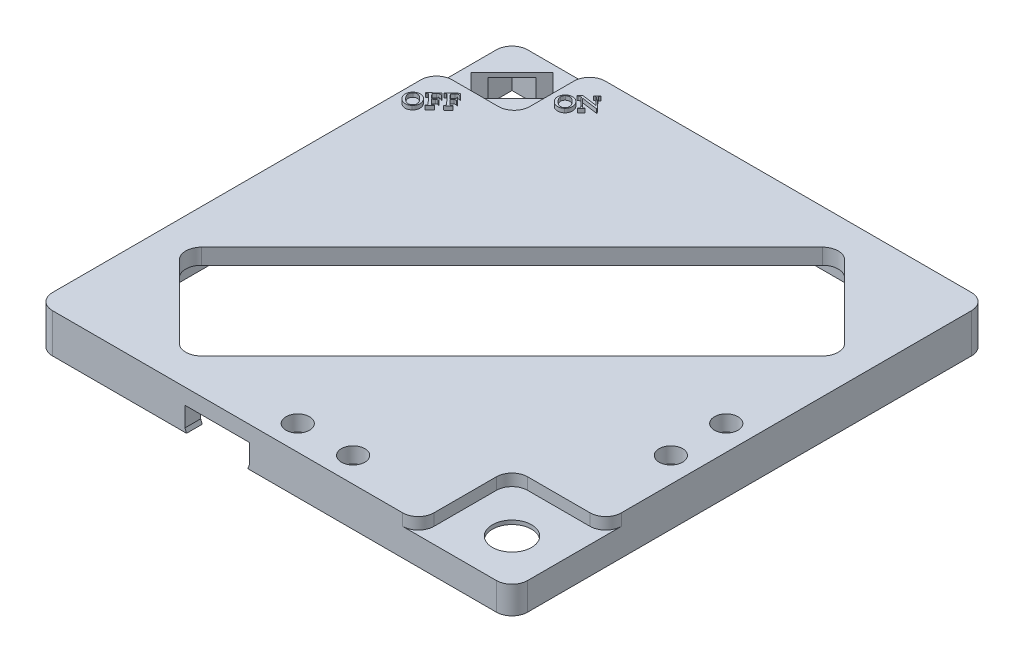
SolidWorks part; units mm, degrees
ref_plane "Front Plane" through (0, 0, 0) normal (0, 0, 1) x (1, 0, 0)
ref_plane "Top Plane" through (0, 0, 0) normal (0, 1, 0) x (1, 0, 0)
ref_plane "Right Plane" through (0, 0, 0) normal (1, 0, 0) x (0, 0, -1)
sketch "Sketch3" plane through (0, 0, 0) normal (0, 1, 0) x (1, 0, 0)
  line L1 (-30.3, -30.3) -> (30.3, -30.3)
  line L2 (-30.3, -30.3) -> (-30.3, 30.3)
  line L3 (-30.3, 30.3) -> (30.3, 30.3)
  line L4 (30.3, -30.3) -> (30.3, 30.3)
  line L5 (-30.3, -30.3) -> (30.3, 30.3) construction
  line L6 (-30.3, 30.3) -> (30.3, -30.3) construction
  point P0 (0, 0)
  dimension "D2" = 60.6
  dimension "D1" = 60.6
extrude "Boss-Extrude1" add sketch "Sketch3" along normal blind 5
sketch "Sketch4" plane through (0, 5, 0) normal (0, 1, 0) x (1, 0, 0)
  line L0 (-15.2028, -27.2236) -> (27.2236, 15.2028)
  line L1 (-15.2028, -27.2236) -> (-27.2236, -15.2028)
  line L2 (27.2236, 15.2028) -> (15.2028, 27.2236)
  line L3 (-27.2236, -15.2028) -> (15.2028, 27.2236)
  line L4 (-15.2028, -27.2236) -> (15.2028, 27.2236) construction
  line L5 (27.2236, 15.2028) -> (-27.2236, -15.2028) construction
  line L6 (30.3, 30.3) -> (-30.3, -30.3) construction
  point P1 (0, 0)
  dimension "D1" = 60
  dimension "D2" = 17
extrude "Cut-Extrude1" cut sketch "Sketch4" against normal through all
sketch "Sketch7" plane through (0, 0, 0) normal (0, -1, 0) x (1, 0, 0)
  line L0 (-30.3, -30.3) -> (-30.3, 30.3) construction
  line L1 (28.3, 28.3) -> (-28.3, 28.3)
  line L2 (28.3, 28.3) -> (28.3, -28.3)
  line L3 (28.3, -28.3) -> (-28.3, -28.3)
  line L4 (-28.3, 28.3) -> (-28.3, -28.3)
  line L5 (28.3, 28.3) -> (-28.3, -28.3) construction
  line L6 (28.3, -28.3) -> (-28.3, 28.3) construction
  line L7 (30.3, -30.3) -> (-30.3, -30.3) construction
  point P0 (0, 0)
  dimension "D1" = 2
  dimension "D2" = 2
extrude "Cut-Extrude11" cut sketch "Sketch7" against normal blind 3
sketch "Sketch9" plane through (0, 3, 0) normal (0, -1, 0) x (1, 0, 0)
  line L0 (30.3, 30.3) -> (-30.3, -30.3) construction
  line L1 (-30.3, 30.3) -> (30.3, 30.3) construction
  line L2 (30.3, 30.3) -> (30.3, -30.3) construction
  line L3 (30.3, 3.33) -> (24.6397, 3.33) construction
  circle A0 centre (27.12, -0.2) radius 1.5
  circle A1 centre (27.12, 6.86) radius 1.5
  circle A2 centre (6.86, 27.12) radius 1.5
  circle A3 centre (-0.2, 27.12) radius 1.5
  dimension "D1" = 3
  dimension "D2" = 30
  dimension "D3" = 3.18
  dimension "D4" = 3.53
extrude "Cut-Extrude12" cut sketch "Sketch9" against normal through all
sketch "Sketch11" plane through (0, 3, 0) normal (0, -1, 0) x (1, 0, 0)
  line L0 (-30.3, -30.3) -> (30.3, 30.3) construction
  line L1 (24.3957, 29.1333) -> (29.1333, 24.3957)
  line L2 (24.3957, 29.1333) -> (19.658, 24.3957)
  line L3 (29.1333, 24.3957) -> (24.3957, 19.658)
  line L4 (19.658, 24.3957) -> (24.3957, 19.658)
  line L5 (24.3957, 29.1333) -> (24.3957, 19.658) construction
  line L6 (29.1333, 24.3957) -> (19.658, 24.3957) construction
  line L7 (-26.5523, -21.3197) -> (-21.3197, -26.5523)
  line L8 (-26.5523, -21.3197) -> (-29.3808, -24.1482)
  line L9 (-21.3197, -26.5523) -> (-24.1482, -29.3808)
  line L10 (-29.3808, -24.1482) -> (-24.1482, -29.3808)
  line L11 (-26.5523, -21.3197) -> (-24.1482, -29.3808) construction
  line L12 (-21.3197, -26.5523) -> (-29.3808, -24.1482) construction
  point P4 (0, 0)
  point P5 (24.3957, 24.3957)
  point P6 (-25.3503, -25.3503)
  dimension "D1" = 6.7
  dimension "D2" = 6.7
  dimension "D3" = 5
  dimension "D4" = 7.4
  dimension "D5" = 4
  dimension "D6" = 5
sketch "Sketch12" plane through (0, 0, 0) normal (0, -1, 0) x (1, 0, 0)
  line L0 (30.3, -30.3) -> (-30.3, -30.3) construction
  line L1 (-30.3, -30.3) -> (-30.3, 30.3) construction
  circle A0 centre (-21.6, -9.72) radius 2.75
  dimension "D1" = 5.5
  dimension "D2" = 20.58
  dimension "D3" = 8.7
extrude "Cut-Extrude14" cut sketch "Sketch12" against normal blind 4.5
sketch "Sketch16" plane through (0, 3, 0) normal (0, -1, 0) x (-1, 0, 0)
  line L0 (-25.7025, 2.9823) -> (-25.7025, 0.2177)
  line L1 (-25.12, -5.46) -> (-25.12, 1.6) construction
  line L2 (-25.12, -1.93) -> (-21.6271, -1.93) construction
  line L3 (-25.7025, -6.8423) -> (-25.7025, -4.0777)
  line L4 (-30.3, -30.3) -> (30.3, 30.3) construction
  line L6 (2.9823, -25.7025) -> (0.2177, -25.7025)
  arc A0 (-25.7025, 0.2177) -> (-25.7025, 2.9823) centre (-25.12, 1.6) ccw
  circle A1 centre (-27.12, 0.2) radius 1.5 construction
  arc A2 (-25.7025, -4.0777) -> (-25.7025, -6.8423) centre (-25.12, -5.46) cw
  arc A4 (0.2177, -25.7025) -> (2.9823, -25.7025) centre (1.6, -25.12) cw
sketch "Sketch17" plane through (0, 3, 0) normal (0, -1, 0) x (1, 0, 0)
  line L0 (18.3515, 18.3515) -> (30.3, 18.3515)
  line L1 (18.3515, 18.3515) -> (18.3515, 30.3)
  line L2 (30.3, 18.3515) -> (30.3, 30.3)
  line L3 (18.3515, 30.3) -> (30.3, 30.3)
  line L4 (18.3515, 18.3515) -> (30.3, 30.3) construction
  line L5 (30.3, 18.3515) -> (18.3515, 30.3) construction
  line L6 (-20.4005, -20.6734) -> (-30.3, -20.6734)
  line L7 (-20.4005, -20.6734) -> (-20.4005, -30.3)
  line L8 (-30.3, -20.6734) -> (-30.3, -30.3)
  line L9 (-20.4005, -30.3) -> (-30.3, -30.3)
  line L10 (-20.4005, -20.6734) -> (-30.3, -30.3) construction
  line L11 (-30.3, -20.6734) -> (-20.4005, -30.3) construction
  line L12 (-30.3, 30.3) -> (30.3, 30.3) construction
  line L13 (30.3, 30.3) -> (30.3, -30.3) construction
  line L14 (30.3, -30.3) -> (-30.3, -30.3) construction
  line L15 (-30.3, -30.3) -> (-30.3, 30.3) construction
  line L16 (-30.3, -30.3) -> (30.3, 30.3) construction
  point P1 (24.3257, 24.3257)
  point P2 (-25.3503, -25.4867)
extrude "Cut-Extrude15" cut sketch "Sketch17" against normal through all
sketch "Sketch20" plane through (0, 0, 30.3) normal (0, 0, 1) x (1, 0, 0)
  line L0 (-7.3, 0) -> (-7.3, 5) construction
  line L1 (-30.3, 0) -> (30.3, 0) construction
  line L2 (-15.2028, 5) -> (15.2028, 5) construction
  line L3 (-11.2, 0) -> (-3.4, 0)
  line L4 (-3.4, 0) -> (-3.2, 0.5)
  line L5 (-3.2, 0.5) -> (-3.2, 3)
  line L6 (-3.2, 3) -> (-11.4, 3)
  line L7 (-11.2, 0) -> (-11.4, 0.5)
  line L8 (-11.4, 0.5) -> (-11.4, 3)
  line L9 (30.3, 3) -> (30.3, 0) construction
  point P6 (-7.3, 3)
  point P14 (-7.3, 3)
  dimension "D1" = 4.1
  dimension "D2" = 3.9
  dimension "D3" = 2.5
  dimension "D4" = 3
  dimension "D5" = 33.5
extrude "Cut-Extrude16" cut sketch "Sketch20" against normal up to next
sketch "Sketch21" plane through (0, 3, 0) normal (0, -1, 0) x (1, 0, 0)
  line L0 (-30.3, -30.3) -> (30.3, 30.3) construction
  line L1 (30.3, 30.3) -> (18.3515, 30.3)
  line L2 (30.3, 30.3) -> (30.3, 18.3515)
  line L3 (30.3, 18.3515) -> (18.3515, 18.3515)
  line L4 (18.3515, 30.3) -> (18.3515, 18.3515)
  line L5 (-30.3, -30.3) -> (-20.3988, -30.3)
  line L6 (-30.3, -30.3) -> (-30.3, -20.3988)
  line L7 (-30.3, -20.3988) -> (-20.3988, -20.3988)
  line L8 (-20.3988, -30.3) -> (-20.3988, -20.3988)
extrude "Boss-Extrude2" add sketch "Sketch21" against normal blind 0.5
sketch "Sketch22" plane through (0, 3.5, 0) normal (0, 1, 0) x (1, 0, 0)
  line L0 (29.1333, -24.3957) -> (19.658, -24.3957) construction
  line L1 (-29.3873, 24.1547) -> (-24.1547, 29.3873)
  line L2 (-29.3873, 24.1547) -> (-26.5458, 21.3132)
  line L3 (-24.1547, 29.3873) -> (-21.3132, 26.5458)
  line L4 (-26.5458, 21.3132) -> (-21.3132, 26.5458)
  line L5 (-29.3873, 24.1547) -> (-21.3132, 26.5458) construction
  line L6 (-24.1547, 29.3873) -> (-26.5458, 21.3132) construction
  circle A0 centre (24.3957, -24.3957) radius 2.5012
  point P5 (-25.3503, 25.3503)
extrude "Cut-Extrude17" cut sketch "Sketch22" against normal through all
fillet "Fillet3" radius 2 14 edges at (-15.2028, 4, 27.2236) (-27.2236, 4, 15.2028) (15.2028, 4, -27.2236) (27.2236, 4, -15.2028) (30.3, 4.25, 18.3515) (18.3515, 4.25, 18.3515) (18.3515, 4.25, 30.3) (-30.3, 4.25, -20.6734) (-20.4005, 4.25, -30.3) (-20.4005, 4.25, -20.6734) (-30.3, 2.5, 30.3) (30.3, 1.75, 30.3) (30.3, 2.5, -30.3) (-30.3, 1.75, -30.3)
sketch "Sketch23" plane through (0, 5, 0) normal (0, 1, 0) x (1, 0, 0)
  line L0 (-28.3401, 14.0998) -> (-13.6313, 27.8716) construction
  text T0 "OFF           ON" font "Times New Roman" height 2
extrude "Boss-Extrude3" add sketch "Sketch23" along normal blind 0.5
equation "\"pcb_w\"= 60.6"
equation "\"pcb_H\"= 60.6"
equation "\"D1@Sketch3\"=\"pcb_H\""
equation "\"D2@Sketch3\"= \"pcb_w\""
equation "\"case_H\"= 5"
equation "\"D1@Boss-Extrude1\"=\"case_H\""
equation "\"AA_L\"= 60"
equation "\"D1@Sketch4\"=\"AA_L\""
equation "\"AA_d\"= 17"
equation "\"D2@Sketch4\"=\"AA_d\""
equation "\"comp_h\"= 3"
equation "\"D1\"= \"comp_h\""
equation "\"D5@Sketch14\"=41-3.9"
